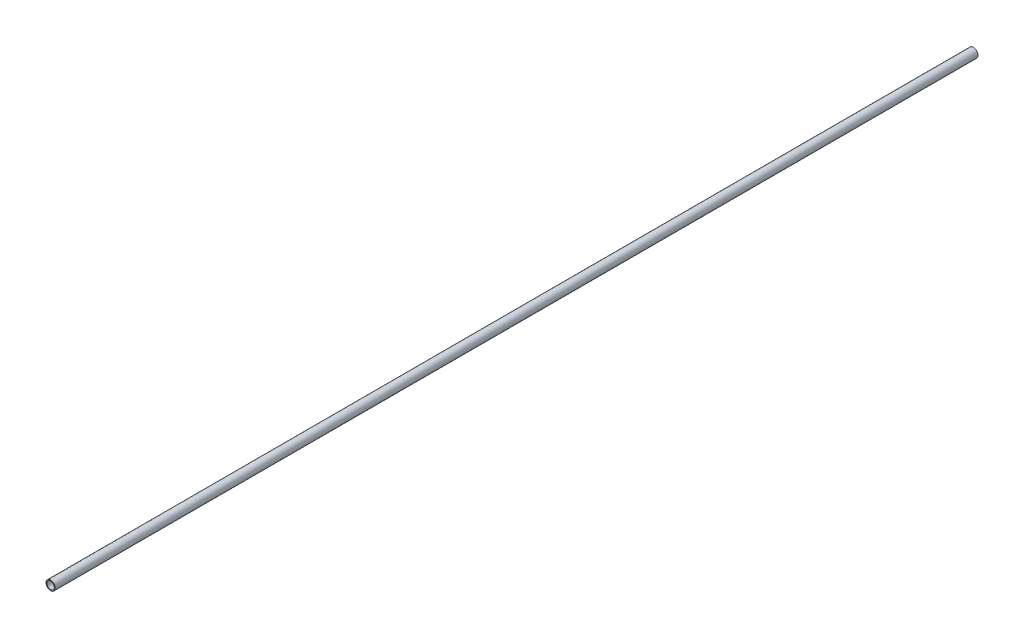
SolidWorks part; units mm, degrees
ref_plane "Front Plane" through (0, 0, 0) normal (0, 0, 1) x (1, 0, 0)
ref_plane "Top Plane" through (0, 0, 0) normal (0, 1, 0) x (1, 0, 0)
ref_plane "Right Plane" through (0, 0, 0) normal (1, 0, 0) x (0, 0, -1)
sketch "Sketch1" plane through (0, 0, 0) normal (0, 0, 1) x (1, 0, 0)
  circle A0 centre (0, 0) radius 10
  dimension "D1" = 20
extrude "Boss-Extrude1" add sketch "Sketch1" along normal blind 2000
sketch "Sketch2" plane through (0, 0, 2000) normal (0, 0, 1) x (1, 0, 0)
  circle A0 centre (0, 0) radius 8
  dimension "D1" = 16
extrude "Cut-Extrude1" cut sketch "Sketch2" against normal blind 2000
